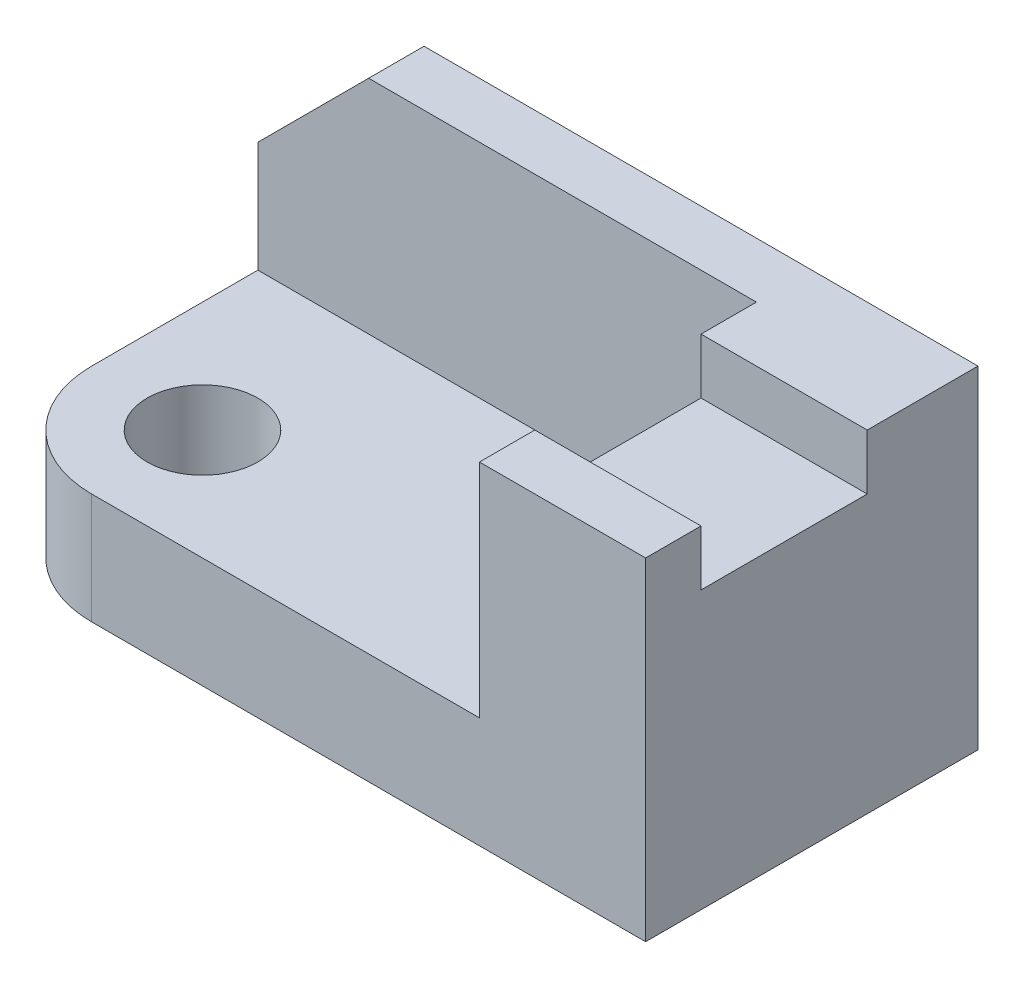
SolidWorks part; units mm, degrees
ref_plane "Front Plane" through (0, 0, 0) normal (0, 0, 1) x (1, 0, 0)
ref_plane "Top Plane" through (0, 0, 0) normal (0, 1, 0) x (1, 0, 0)
ref_plane "Right Plane" through (0, 0, 0) normal (1, 0, 0) x (0, 0, -1)
sketch "Sketch2" plane through (0, 0, 0) normal (0, 1, 0) x (1, 0, 0)
  line L1 (0, 0) -> (-120, 0)
  line L2 (0, 0) -> (0, -60)
  line L3 (0, -60) -> (-120, -60)
  line L4 (-120, 0) -> (-120, -60)
  dimension "D1" = 120
  dimension "D2" = 60
extrude "Boss-Extrude1" add sketch "Sketch2" against normal blind 20
sketch "Sketch3" plane through (0, 0, 0) normal (0, 1, 0) x (1, 0, 0)
  line L0 (-120, -10) -> (-30, -10)
  line L1 (-120, 0) -> (-120, -60) construction
  line L2 (-30, -10) -> (-30, -60)
  line L3 (-120, -60) -> (0, -60) construction
  line L4 (-30, -60) -> (0, -60)
  line L5 (0, 0) -> (0, -60)
  line L6 (-120, 0) -> (-120, -10)
  line L7 (-120, 0) -> (0, 0)
  dimension "D1" = 30
  dimension "D2" = 10
extrude "Boss-Extrude2" add sketch "Sketch3" along normal blind 40
fillet "Fillet1" radius 20 1 edges at (-120, -10, 60)
chamfer "Chamfer1" distance 20 angle 45 1 edges at (-120, 40, 5)
ref_plane "Plane1" through (-30, 40, 10) normal (0, 0, 1) x (1, 0, 0)
sketch "Sketch8" plane through (0, 40, 0) normal (0, 1, 0) x (1, 0, 0)
  line L7 (-30, -10) -> (-30, -60) construction
  line L8 (-30, -20) -> (0, -20)
  line L9 (-30, -20) -> (-30, -50)
  line L10 (-30, -50) -> (0, -50)
  line L11 (0, -20) -> (0, -50)
  line L12 (0, -60) -> (0, 0) construction
  line L13 (-100, -10) -> (-30, -10) construction
  line L14 (-30, -60) -> (0, -60) construction
  dimension "D1" = 10
  dimension "D2" = 10
extrude "Cut-Extrude1" cut sketch "Sketch8" against normal blind 10
sketch "Sketch10" plane through (0, 0, 0) normal (0, 1, 0) x (1, 0, 0)
  circle A0 centre (-100, -40) radius 10
  dimension "D1" = 20
sketch "Sketch11" plane through (0, 0, 0) normal (0, 1, 0) x (1, 0, 0)
  circle A0 centre (-100, -40) radius 10
  dimension "D1" = 20
extrude "Cut-Extrude3" cut sketch "Sketch11" against normal through all
